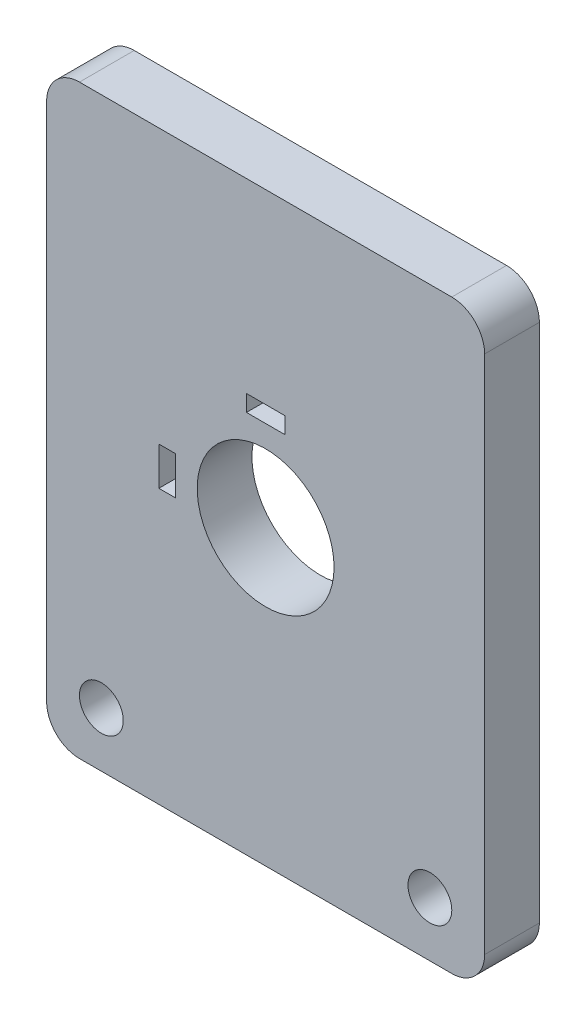
SolidWorks part; units mm, degrees
material "ﾎﾟﾘ塩化ﾋﾞﾆﾙ(PVC)硬質"
ref_plane "正面" through (0, 0, 0) normal (0, 0, 1) x (1, 0, 0)
ref_plane "平面" through (0, 0, 0) normal (0, 1, 0) x (1, 0, 0)
ref_plane "右側面" through (0, 0, 0) normal (1, 0, 0) x (0, 0, -1)
sketch "ｽｹｯﾁ1" plane through (0, 0, 0) normal (0, 0, 1) x (1, 0, 0)
  line L0 (40, 5) -> (0, 5) construction
  line L1 (0, 0) -> (40, 0)
  line L2 (0, 0) -> (0, 53.5)
  line L3 (0, 53.5) -> (40, 53.5)
  line L4 (40, 0) -> (40, 53.5)
  line L5 (40, 26.75) -> (0, 26.75) construction
  line L6 (20, 0) -> (20, 53.5) construction
  line L7 (20, 26.75) -> (20, 33) construction
  line L8 (18.25, 35) -> (18.25, 36.5)
  line L9 (18.25, 36.5) -> (21.75, 36.5)
  line L10 (21.75, 36.5) -> (21.75, 35)
  line L11 (21.75, 35) -> (18.25, 35)
  line L13 (11.75, 25) -> (10.25, 25)
  line L14 (11.75, 25) -> (11.75, 28.5)
  line L15 (11.75, 28.5) -> (10.25, 28.5)
  line L16 (10.25, 25) -> (10.25, 28.5)
  line L17 (11.75, 25) -> (10.25, 28.5) construction
  line L18 (11.75, 28.5) -> (10.25, 25) construction
  line L19 (28, 41) -> (12, 41) construction
  line L20 (28, 41) -> (28, 12.5) construction
  line L21 (28, 12.5) -> (12, 12.5) construction
  line L22 (12, 41) -> (12, 12.5) construction
  line L23 (28, 41) -> (12, 12.5) construction
  line L24 (28, 12.5) -> (12, 41) construction
  circle A2 centre (20, 26.75) radius 6.25
  circle A3 centre (35, 5) radius 2
  circle A4 centre (5, 5) radius 2
  point P17 (13.75, 26.75)
  point P25 (11, 26.75)
  point P32 (20, 28.8309)
  dimension "D2" = 30
  dimension "D3" = 5
  dimension "D6" = 1.5
  dimension "D7" = 12.5
  dimension "D8" = 3.5
  dimension "D9" = 9.75
  dimension "D4" = 4
  dimension "D14" = 7.5
  dimension "D15" = 5
  dimension "D5" = 9.75
  dimension "D10" = 3.5
  dimension "D11" = 1.5
  dimension "D12" = 28.5
  dimension "D13" = 16
extrude "ﾎﾞｽ - 押し出し1" add sketch "ｽｹｯﾁ1" along normal blind 5
fillet "ﾌｨﾚｯﾄ1" radius 3 4 edges at (40, 0, 2.5) (40, 53.5, 2.5) (0, 0, 2.5) (0, 53.5, 2.5)
